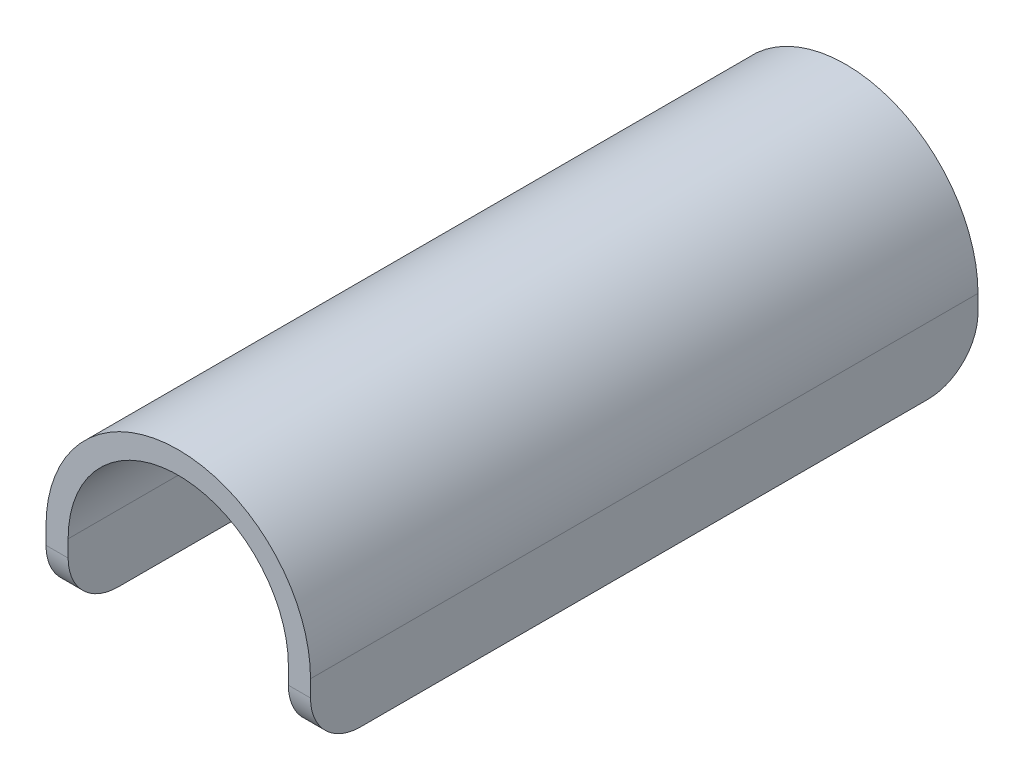
SolidWorks part; units mm, degrees
ref_plane "Piano frontale" through (0, 0, 0) normal (0, 0, 1) x (1, 0, 0)
ref_plane "Piano superiore" through (0, 0, 0) normal (0, 1, 0) x (1, 0, 0)
ref_plane "Piano destro" through (0, 0, 0) normal (1, 0, 0) x (0, 0, -1)
sketch "Schizzo1" plane through (0, 0, 0) normal (0, 0, 1) x (1, 0, 0)
  line L3 (-39.628, 0) -> (-33, 0)
  line L4 (33, 0) -> (39.628, 0)
  arc A4 (33, 0) -> (-33, 0) centre (0, 0) ccw
  arc A5 (39.628, 0) -> (-39.628, 0) centre (0, 0) ccw
extrude "Estrusione-Estrusione2" add sketch "Schizzo1" along normal blind 200
sketch "Schizzo2" plane through (0, 0, 0) normal (0, 0, 1) x (1, 0, 0)
  line L0 (-39.628, 0) -> (-39.628, -20)
  line L1 (-33, 0) -> (-33, -20)
  line L2 (-33, -20) -> (-39.628, -20)
  line L3 (33, 0) -> (33, -20)
  line L4 (33, -20) -> (39.628, -20)
  line L5 (39.628, -20) -> (39.628, 0)
  line L6 (39.628, 0) -> (33, 0)
  line L7 (-39.628, 0) -> (-33, 0)
extrude "Estrusione-Estrusione3" add sketch "Schizzo2" along normal up to vertex (200 mm away) up to point (-39.628, 0, 200)
fillet "Raccordo3" radius 15 4 edges at (-36.314, -20, 0) (-36.314, -20, 200) (36.314, -20, 0) (36.314, -20, 200)
